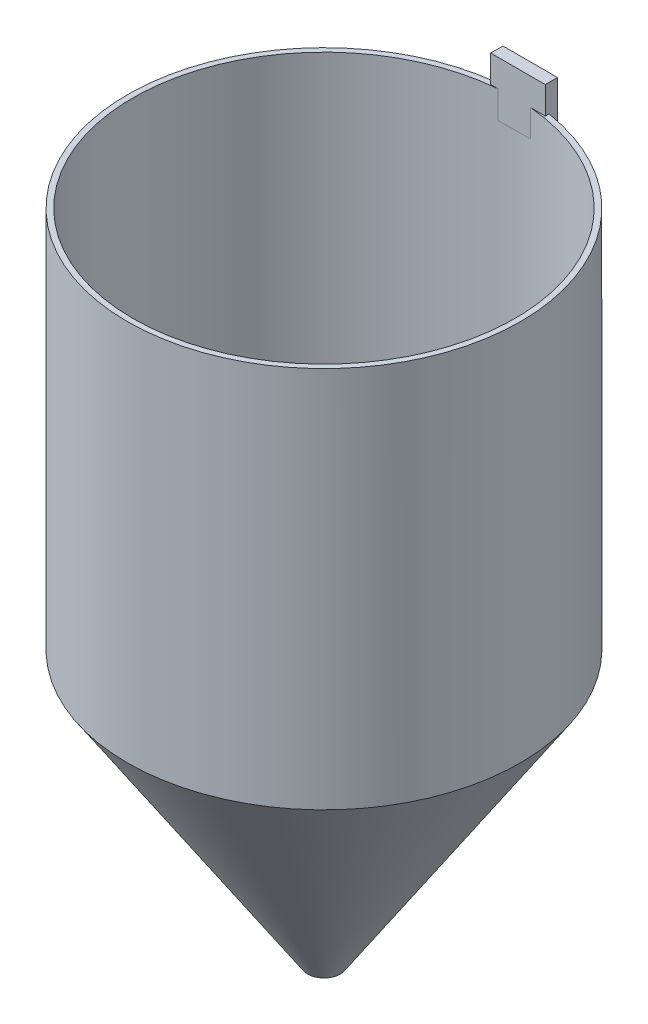
SolidWorks part; units mm, degrees
material "ABS"
ref_plane "Front Plane" through (0, 0, 0) normal (0, 0, 1) x (1, 0, 0)
ref_plane "Top Plane" through (0, 0, 0) normal (0, 1, 0) x (1, 0, 0)
ref_plane "Right Plane" through (0, 0, 0) normal (1, 0, 0) x (0, 0, -1)
sketch "Sketch1" plane through (0, 0, 0) normal (0, 0, 1) x (1, 0, 0)
  line L0 (2.3108, 103.018) -> (2.3108, 34.02)
  line L1 (2.3108, 34.02) -> (-32.6892, 34.02)
  line L2 (-32.6892, 34.02) -> (-32.6892, 33.02)
  line L3 (-32.6892, 33.02) -> (2.3108, 33.02)
  line L4 (2.3108, 33.02) -> (-29.6864, -16.982)
  line L5 (-29.6864, -16.982) -> (3.3108, 33.018)
  line L6 (3.3108, 33.018) -> (3.3108, 103.018)
  line L7 (3.3108, 103.018) -> (2.3108, 103.018)
  dimension "D1" = 1
  dimension "D2" = 1
  dimension "D3" = 1
  dimension "D4" = 70
  dimension "D5" = 50
  dimension "D6" = 35
revolve "Revolve1" add sketch "Sketch1" angle 360 about L2
sketch "Sketch2" plane through (0, 34.02, 0) normal (0, 1, 0) x (1, 0, 0)
  circle A0 centre (-32.6892, 0) radius 2
  circle A1 centre (-14.5838, 17.2394) radius 5
  dimension "D1" = 4
  dimension "D2" = 10
  dimension "D3" = 25
extrude "Cut-Extrude1" cut sketch "Sketch2" against normal blind 3
sketch "Sketch3" plane through (0, 103.018, 0) normal (0, 1, 0) x (1, 0, 0)
  line L1 (-37.0162, 34.8749) -> (-27.0162, 34.8749)
  line L2 (-37.0162, 34.8749) -> (-37.0162, 37.1125)
  line L3 (-37.0162, 37.1125) -> (-27.0162, 37.1125)
  line L4 (-27.0162, 34.8749) -> (-27.0162, 37.1125)
  line L5 (-37.0162, 34.8749) -> (-27.0162, 37.1125) construction
  line L6 (-37.0162, 37.1125) -> (-27.0162, 34.8749) construction
  circle A0 centre (-32.6892, 0) radius 36 construction
  point P0 (-32.0162, 35.9937)
  dimension "D1" = 10
extrude "Boss-Extrude1" add sketch "Sketch3" along normal mid plane 10
